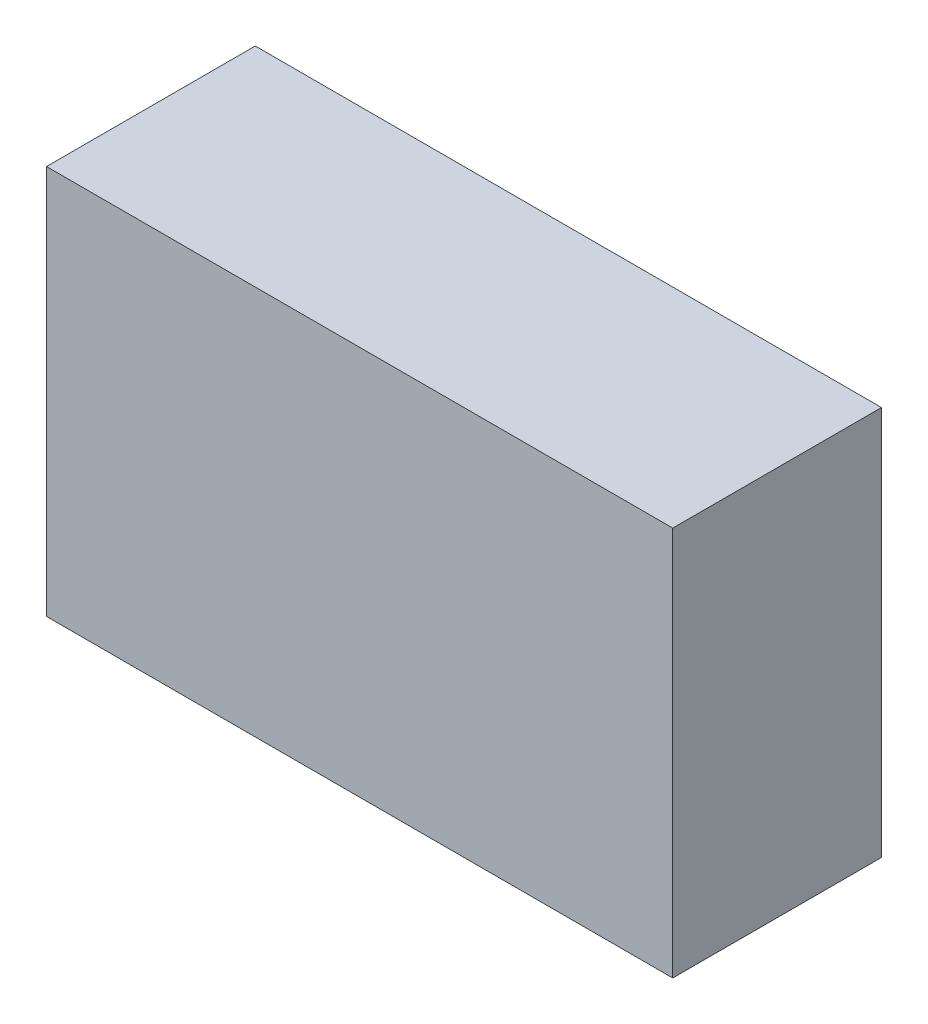
SolidWorks part; units mm, degrees
ref_plane "Front Plane" through (0, 0, 0) normal (0, 0, 1) x (1, 0, 0)
ref_plane "Top Plane" through (0, 0, 0) normal (0, 1, 0) x (1, 0, 0)
ref_plane "Right Plane" through (0, 0, 0) normal (1, 0, 0) x (0, 0, -1)
sketch "Sketch1" plane through (0, 0, 0) normal (0, 0, 1) x (1, 0, 0)
  line L1 (-22.5, -14) -> (22.5, -14)
  line L2 (-22.5, -14) -> (-22.5, 14)
  line L3 (-22.5, 14) -> (22.5, 14)
  line L4 (22.5, -14) -> (22.5, 14)
extrude "REFERENCE_ENVELOPE_NOT_MANUFACTURING" add sketch "Sketch1" along normal blind 15 from offset 0
